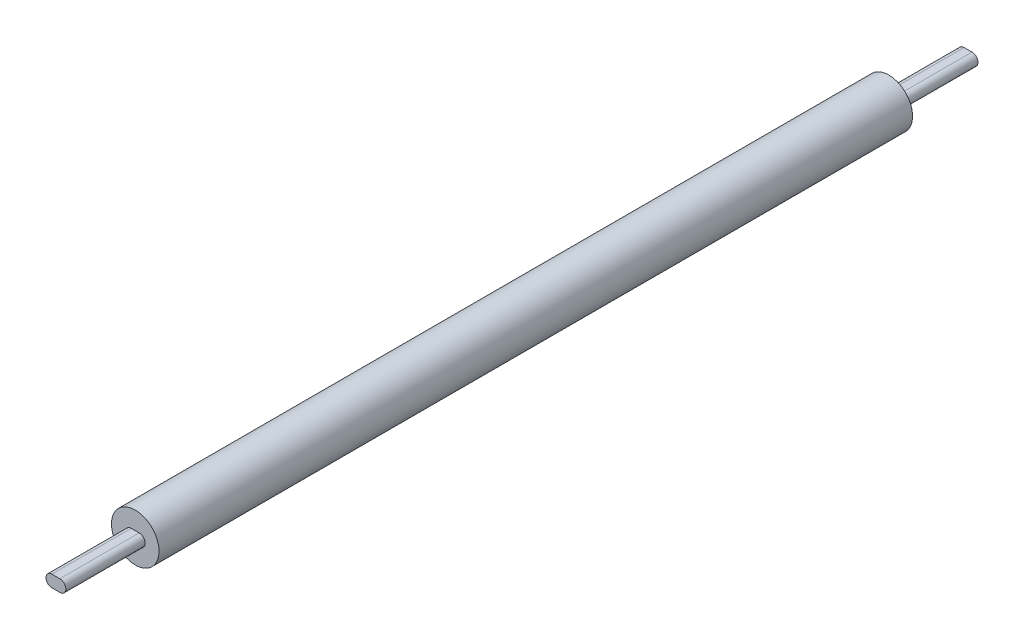
SolidWorks part; units mm, degrees
ref_plane "Front Plane" through (0, 0, 0) normal (0, 0, 1) x (1, 0, 0)
ref_plane "Top Plane" through (0, 0, 0) normal (0, 1, 0) x (1, 0, 0)
ref_plane "Right Plane" through (0, 0, 0) normal (1, 0, 0) x (0, 0, -1)
sketch "Esquisse1" plane through (0, 0, 0) normal (0, 0, 1) x (1, 0, 0)
  circle A0 centre (0, 0) radius 6
  dimension "D1" = 12
extrude "Boss.-Extru.1" add sketch "Esquisse1" along normal blind 190
sketch "Esquisse2" plane through (0, 0, 190) normal (0, 0, 1) x (1, 0, 0)
  line L0 (-1, 0) -> (1, 0) construction
  line L1 (-1, 1.5) -> (1, 1.5)
  line L2 (-1, -1.5) -> (1, -1.5)
  arc A0 (-1, 1.5) -> (-1, -1.5) centre (-1, 0) ccw
  arc A1 (1, -1.5) -> (1, 1.5) centre (1, 0) ccw
  circle A2 centre (0, 0) radius 6 construction
  point P3 (0, 0)
  dimension "D2" = 1.5
  dimension "D1" = 2
extrude "Boss.-Extru.2" add sketch "Esquisse2" along normal blind 20
sketch "Esquisse3" plane through (0, 0, 0) normal (0, 0, -1) x (-1, 0, 0)
  line L0 (-1, 0) -> (1, 0) construction
  line L1 (-1, 1.5) -> (1, 1.5)
  line L2 (-1, -1.5) -> (1, -1.5)
  arc A0 (-1, 1.5) -> (-1, -1.5) centre (-1, 0) ccw
  arc A1 (1, -1.5) -> (1, 1.5) centre (1, 0) ccw
  circle A2 centre (0, 0) radius 6 construction
  point P4 (0, 0)
  point P11 (0, 0)
  dimension "D2" = 1.5
  dimension "D1" = 2
extrude "Boss.-Extru.3" add sketch "Esquisse3" along normal blind 20
